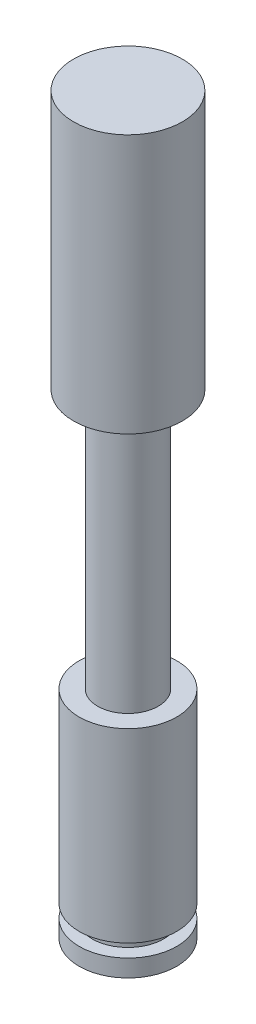
SolidWorks part; units mm, degrees
ref_plane "Front Plane" through (0, 0, 0) normal (0, 0, 1) x (1, 0, 0)
ref_plane "Top Plane" through (0, 0, 0) normal (0, 1, 0) x (1, 0, 0)
ref_plane "Right Plane" through (0, 0, 0) normal (1, 0, 0) x (0, 0, -1)
sketch "Sketch1" plane through (0, 0, 0) normal (0, 1, 0) x (1, 0, 0)
  line L0 (0, 0) -> (0, 3.3) construction
  line L1 (0, 0) -> (-6.2902, 0) construction
  circle A0 centre (0, 0) radius 5.65
  dimension "D1" = 11.3
extrude "Boss-Extrude1" add sketch "Sketch1" along normal blind 2 contours A0
sketch "Sketch2" plane through (0, 2, 0) normal (0, 1, 0) x (1, 0, 0)
  circle A0 centre (0, 0) radius 4.15
  dimension "D1" = 8.3
extrude "Boss-Extrude2" add sketch "Sketch2" along normal blind 1.5
sketch "Sketch3" plane through (0, 3.5, 0) normal (0, 1, 0) x (1, 0, 0)
  circle A0 centre (0, 0) radius 5.65
  dimension "D1" = 11.3
extrude "Boss-Extrude3" add sketch "Sketch3" along normal blind 21.5
sketch "Sketch4" plane through (0, 25, 0) normal (0, 1, 0) x (1, 0, 0)
  circle A0 centre (0, 0) radius 3.5
  dimension "D1" = 7
extrude "Boss-Extrude4" add sketch "Sketch4" along normal blind 30
sketch "Sketch5" plane through (0, 55, 0) normal (0, 1, 0) x (1, 0, 0)
  circle A0 centre (0, 0) radius 6.3
  dimension "D1" = 12.6
extrude "Boss-Extrude5" add sketch "Sketch5" along normal blind 30
